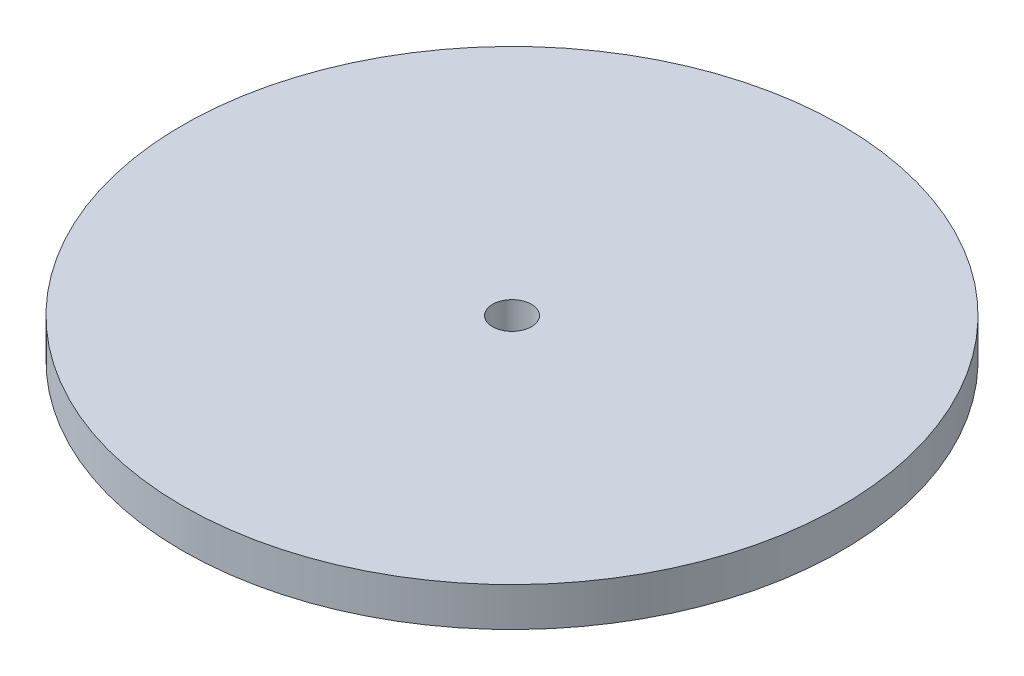
SolidWorks part; units mm, degrees
ref_plane "Front Plane" through (0, 0, 0) normal (0, 0, 1) x (1, 0, 0)
ref_plane "Top Plane" through (0, 0, 0) normal (0, 1, 0) x (1, 0, 0)
ref_plane "Right Plane" through (0, 0, 0) normal (1, 0, 0) x (0, 0, -1)
sketch "Sketch1" plane through (0, 0, 0) normal (0, 1, 0) x (1, 0, 0)
  circle A0 centre (0, 0) radius 107.5
  circle A1 centre (0, 0) radius 6.35
  dimension "D1" = 215
  dimension "D2" = 12.7
extrude "Boss-Extrude1" add sketch "Sketch1" along normal blind 12.7
